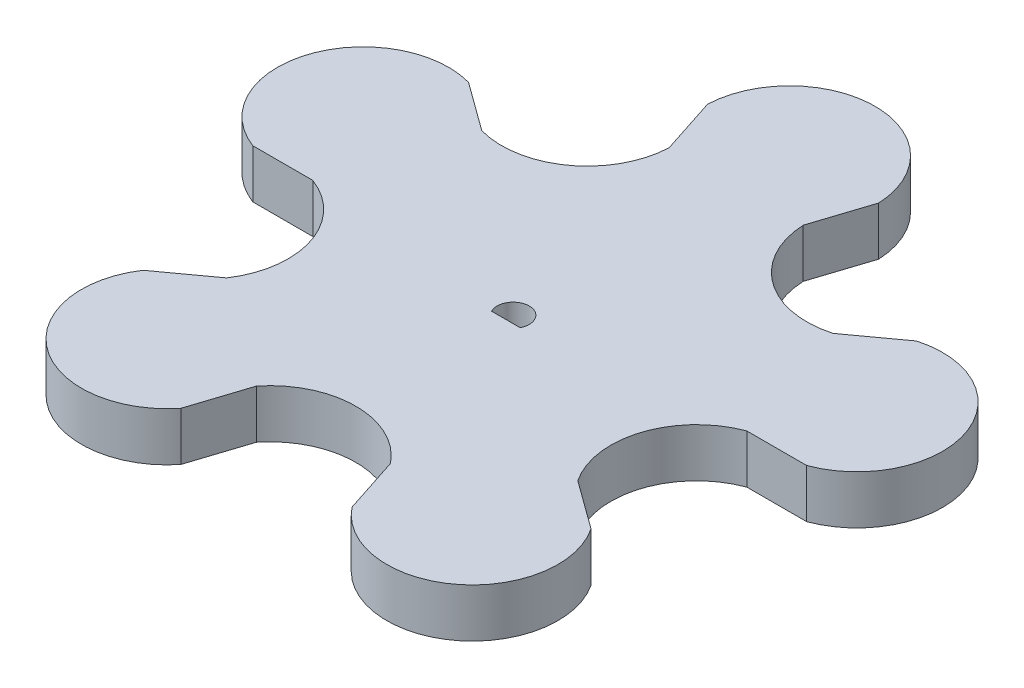
SolidWorks part; units mm, degrees
ref_plane "Front Plane" through (0, 0, 0) normal (0, 0, 1) x (1, 0, 0)
ref_plane "Top Plane" through (0, 0, 0) normal (0, 1, 0) x (1, 0, 0)
ref_plane "Right Plane" through (0, 0, 0) normal (1, 0, 0) x (0, 0, -1)
sketch "Sketch2" plane through (0, 0, 0) normal (0, 1, 0) x (1, 0, 0)
  line L0 (0, 0) -> (0, 16.9342) construction
  line L1 (-5.5828, 34.124) -> (-4.3753, 30.4076)
  line L2 (-4.3753, 30.4076) -> (-4.3565, 30.3846)
  line L3 (-14.616, 6.3226) -> (-11.4547, 8.6195)
  line L4 (-18.0664, 16.9418) -> (-14.1588, 16.9418)
  line L5 (-14.616, 27.561) -> (-11.4547, 25.2641)
  line L6 (5.5828, 34.124) -> (4.3753, 30.4076)
  line L7 (14.616, 27.561) -> (11.4547, 25.2641)
  line L8 (18.0664, 16.9418) -> (14.1588, 16.9418)
  line L9 (14.1588, 16.9418) -> (14.1782, 17.0613)
  line L10 (14.616, 6.3226) -> (11.4547, 8.6195)
  line L11 (11.4547, 8.6195) -> (11.6097, 8.7137)
  line L12 (5.5828, -0.2404) -> (4.3753, 3.476)
  line L13 (-5.5828, -0.2404) -> (-4.3753, 3.476)
  circle A0 centre (0, 16.9342) radius 16.9442 construction
  arc A1 (-14.616, 6.3226) -> (-5.5828, -0.2404) centre (-9.9581, 3.2356) ccw
  arc A3 (-14.616, 27.561) -> (-18.0664, 16.9418) centre (-16.1126, 22.1771) ccw
  arc A7 (18.0664, 16.9418) -> (14.616, 27.561) centre (16.1126, 22.1771) ccw
  arc A9 (5.5828, -0.2404) -> (14.616, 6.3226) centre (9.9581, 3.2356) ccw
  arc A10 (-11.4547, 25.2641) -> (-4.3753, 30.4076) centre (-9.9581, 30.648) ccw
  arc A12 (-11.4547, 8.6195) -> (-14.1588, 16.9418) centre (-16.1126, 11.7065) ccw
  arc A14 (4.3753, 3.476) -> (-4.3753, 3.476) centre (0, 0) ccw
  arc A16 (14.1588, 16.9418) -> (11.4547, 8.6195) centre (16.1126, 11.7065) ccw
  arc A18 (5.5828, 34.124) -> (-5.5828, 34.124) centre (0, 33.8836) ccw
  arc A19 (4.3753, 30.4076) -> (11.4547, 25.2641) centre (9.9581, 30.648) ccw
  point P25 (0, 16.9418)
extrude "Boss-Extrude1" add sketch "Sketch2" along normal blind 3.175
sketch "Sketch3" plane through (0, 3.175, 0) normal (0, 1, 0) x (1, 0, 0)
  line L0 (0, 5.588) -> (10.7981, 13.4333) construction
  line L1 (10.9624, 13.8748) -> (6.6736, 26.1272) construction
  line L2 (6.6736, 26.1272) -> (-6.6736, 26.1272) construction
  line L3 (-6.6736, 26.1272) -> (-10.7981, 13.4333) construction
  line L4 (-10.7981, 13.4333) -> (0, 5.588) construction
  line L5 (0, 26.1272) -> (0, 5.588) construction
  line L6 (0, 16.9054) -> (0, 15.3814) construction
  line L7 (-0.9333, 15.3814) -> (0.9333, 15.3814)
  arc A0 (0.9333, 15.3814) -> (-0.9333, 15.3814) centre (0, 15.8576) ccw
  arc A15 (4.3753, 3.476) -> (-4.3753, 3.476) centre (0, 0) ccw construction
  arc A16 (14.1588, 16.9418) -> (11.4547, 8.6195) centre (16.1126, 11.7065) ccw construction
  arc A17 (4.3753, 30.4076) -> (11.4547, 25.2641) centre (9.9581, 30.648) ccw construction
  arc A18 (-11.4547, 25.2641) -> (-4.3753, 30.4076) centre (-9.9581, 30.648) ccw construction
  arc A19 (-11.4547, 8.6195) -> (-14.1588, 16.9418) centre (-16.1126, 11.7065) ccw construction
extrude "Cut-Extrude1" cut sketch "Sketch3" against normal through all
sketch "Sketch4" plane through (0, 3.175, 0) normal (0, 1, 0) x (1, 0, 0)
  circle A0 centre (0, 15.8576) radius 18.7242 construction
